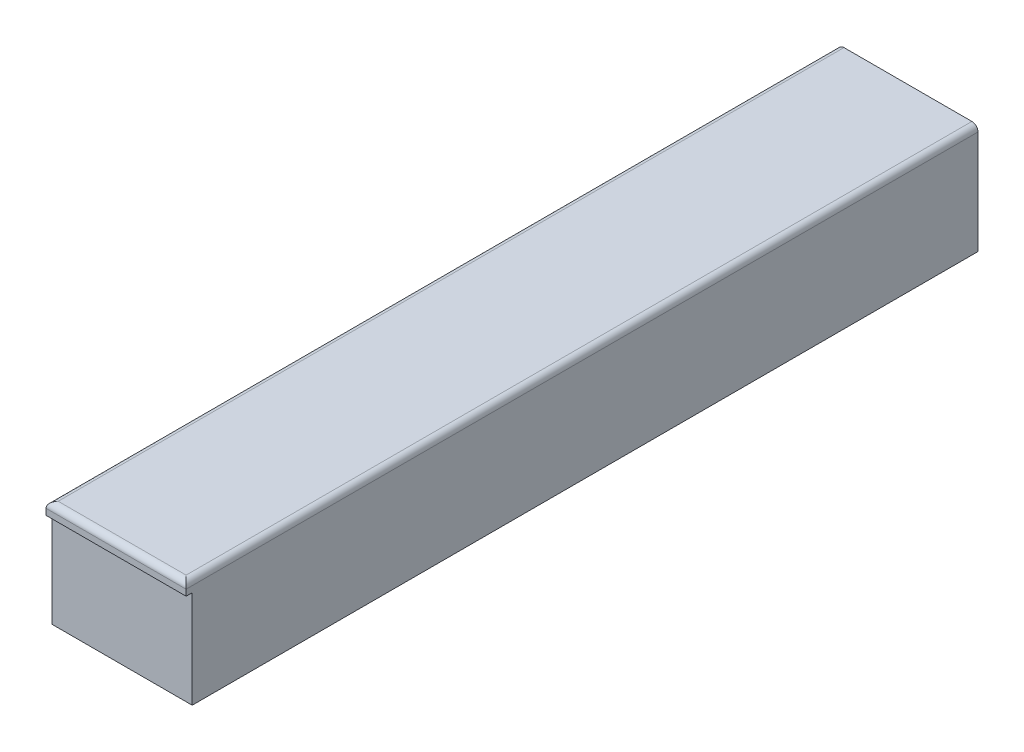
SolidWorks part; units mm, degrees
material "Pino"
ref_plane "Alzado" through (0, 0, 0) normal (0, 0, 1) x (1, 0, 0)
ref_plane "Planta" through (0, 0, 0) normal (0, 1, 0) x (1, 0, 0)
ref_plane "Vista lateral" through (0, 0, 0) normal (1, 0, 0) x (0, 0, -1)
sketch "Croquis2" plane through (0, 0, 0) normal (0, 1, 0) x (1, 0, 0)
  line L1 (0, 0) -> (23, 0)
  line L2 (0, 0) -> (0, 130)
  line L3 (0, 130) -> (23, 130)
  line L4 (23, 0) -> (23, 130)
  line L5 (23, 130) -> (14, 130)
  line L6 (23, 130) -> (23, 50)
  dimension "D1" = 23
  dimension "D2" = 130
extrude "Saliente-Extruir1" add sketch "Croquis2" along normal blind 18
sketch "Croquis3" plane through (0, 0, 0) normal (0, 0, 1) x (1, 0, 0)
  line L0 (23, 18) -> (23, 0) construction
  line L1 (0, 0) -> (23, 0)
  line L2 (0, 0) -> (0, 16)
  line L3 (0, 16) -> (23, 16)
  line L4 (23, 0) -> (23, 16)
extrude "Cortar-Extruir1" cut sketch "Croquis3" against normal blind 1
fillet "Redondeo1" radius 1 3 edges at (11.5, 18, 0) (23, 18, -65) (0, 18, -65)
